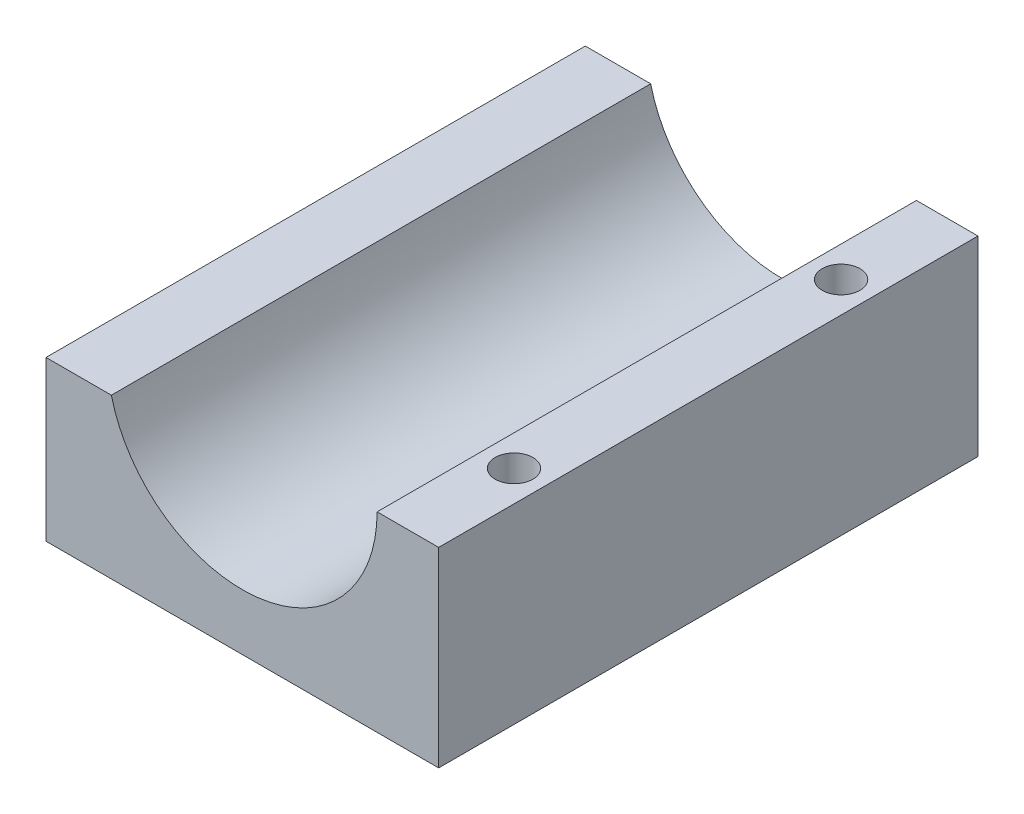
SolidWorks part; units mm, degrees
ref_plane "Front Plane" through (0, 0, 0) normal (0, 0, 1) x (1, 0, 0)
ref_plane "Top Plane" through (0, 0, 0) normal (0, 1, 0) x (1, 0, 0)
ref_plane "Right Plane" through (0, 0, 0) normal (1, 0, 0) x (0, 0, -1)
sketch "Sketch2" plane through (0, 0, 0) normal (0, 1, 0) x (1, 0, 0)
  line L1 (0, 0) -> (18.5, 0)
  line L2 (0, 0) -> (0, 25.41)
  line L3 (0, 25.41) -> (18.5, 25.41)
  line L4 (18.5, 0) -> (18.5, 25.41)
extrude "Boss-Extrude1" add sketch "Sketch2" along normal blind 9
sketch "Sketch6" plane through (0, 0, 0) normal (0, 0, 1) x (1, 0, 0)
  line L0 (0, 9) -> (18.5, 9) construction
  line L1 (2.9, 9) -> (15.6, 9)
  arc A0 (2.9, 9) -> (15.6, 9) centre (9.25, 9) ccw
extrude "Cut-Extrude1" cut sketch "Sketch6" against normal blind 25.41
sketch "Sketch7" plane through (0, 0, 0) normal (0, -1, 0) x (-1, 0, 0)
  line L0 (0, 0) -> (0, 5)
  line L1 (0, 25.41) -> (0, 0) construction
  line L2 (0, 5) -> (-18.5, 5)
  line L3 (-18.5, 0) -> (-18.5, 25.41) construction
  line L4 (0, 25.41) -> (0, 20.41)
  line L5 (0, 20.41) -> (-18.5, 20.41)
hole_wizard "#2-56 Tapped Hole1" positions "Sketch8" profile "Sketch9" tap size "#2-56" standard "ANSI Inch"
sketch "Sketch8" plane through (0, 0, 0) normal (0, -1, 0) x (-1, 0, 0)
  line L0 (0, 20.41) -> (-18.5, 20.41) construction
  line L1 (0, 5) -> (-18.5, 5) construction
  point P0 (-9.25, 20.41)
  point P4 (-9.25, 5)
sketch "Sketch9" plane through (9.25, 0, -20.41) normal (1, 0, 0) x (0, 0, -1)
  line L0 (0, 0) -> (0, 2.5)
  line L1 (0, 2.5) -> (0.889, 1.9658)
  line L2 (0.889, 1.9658) -> (0.889, 0)
  line L5 (0.889, 0) -> (0, 0)
  line L10 (0, 2.5) -> (-0.889, 1.9658) construction
  line L11 (0, -6.35) -> (0, 107.95) construction
  dimension "Tap Drill Dia." = 1.778
  dimension "Tap Drill Depth" = 2.5
  dimension "Drill Angle" = 118
cosmetic thread "Hole Thread1" parameters "D1"=4.37, "D2"=2.1844
cosmetic thread "Hole Thread2" parameters "D1"=4.37, "D2"=2.1844
sketch "Sketch10" plane through (0, 9, 0) normal (0, 1, 0) x (1, 0, 0)
  line L0 (17.05, 25.41) -> (17.05, 20.41)
  line L1 (18.5, 25.41) -> (15.6, 25.41) construction
  line L2 (17.05, 0) -> (17.05, 5)
  line L3 (15.6, 0) -> (18.5, 0) construction
hole_wizard "#2-56 Tapped Hole2" positions "Sketch11" profile "Sketch12" tap size "#2-56" standard "ANSI Inch"
sketch "Sketch11" plane through (0, 9, 0) normal (0, 1, 0) x (1, 0, 0)
  point P0 (17.05, 20.41)
  point P3 (17.05, 5)
sketch "Sketch12" plane through (17.05, 9, -20.41) normal (1, 0, 0) x (0, 0, 1)
  line L0 (0, 0) -> (0, 4)
  line L1 (0, 4) -> (0.889, 3.4658)
  line L2 (0.889, 3.4658) -> (0.889, 0)
  line L5 (0.889, 0) -> (0, 0)
  line L10 (0, 4) -> (-0.889, 3.4658) construction
  line L11 (0, -6.35) -> (0, 107.95) construction
  dimension "Tap Drill Dia." = 1.778
  dimension "Tap Drill Depth" = 4
  dimension "Drill Angle" = 118
cosmetic thread "Hole Thread3" parameters "D1"=4.37, "D2"=2.1844
cosmetic thread "Hole Thread4" parameters "D1"=4.37, "D2"=2.1844
sketch "Sketch14" plane through (0, 0, -25.41) normal (0, 0, -1) x (-1, 0, 0)
  line L0 (0, 9) -> (0, 7.5)
  line L1 (0, 9) -> (0, 0) construction
  line L2 (0, 7.5) -> (-3.2467, 7.5)
  line L3 (-3.2467, 7.5) -> (-2.9, 9)
extrude "Cut-Extrude3" cut sketch "Sketch14" against normal blind 25.41 and the other way through all flip side to cut
